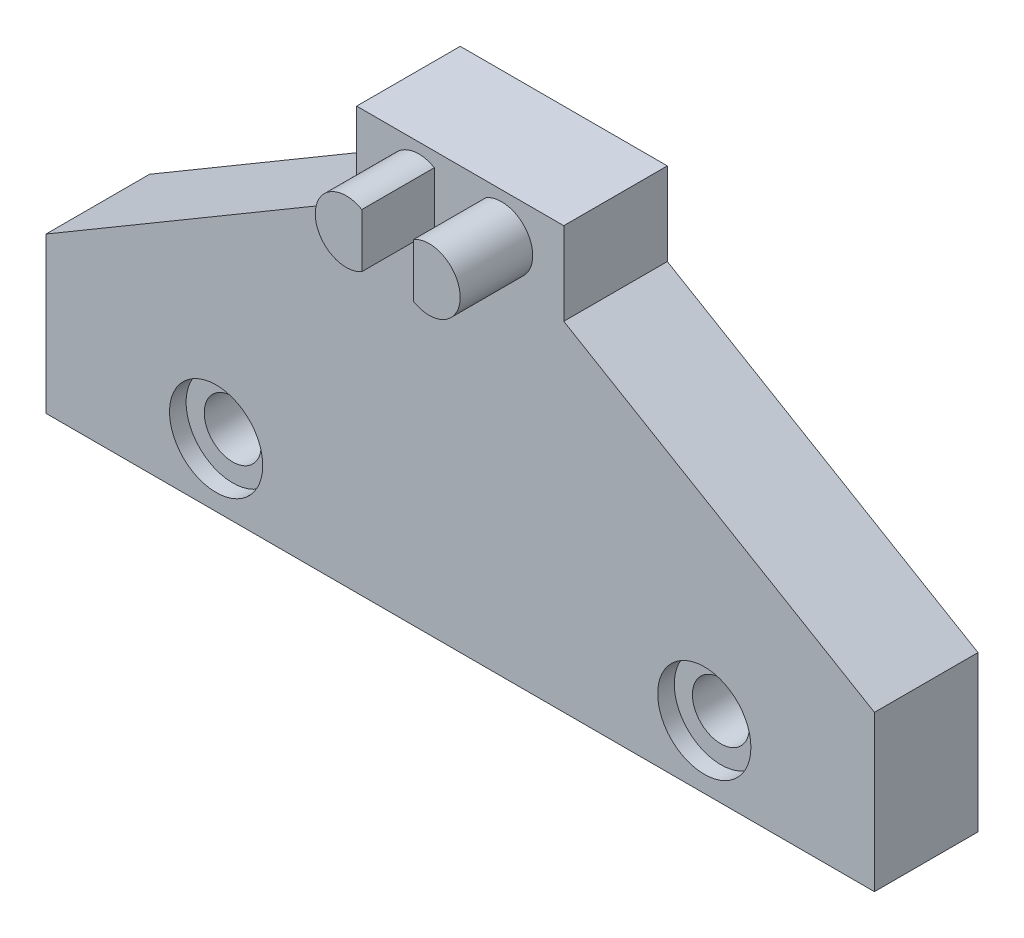
SolidWorks part; units mm, degrees
ref_plane "Front Plane" through (0, 0, 0) normal (0, 0, 1) x (1, 0, 0)
ref_plane "Top Plane" through (0, 0, 0) normal (0, 1, 0) x (1, 0, 0)
ref_plane "Right Plane" through (0, 0, 0) normal (1, 0, 0) x (0, 0, -1)
sketch "Sketch2" plane through (0, 0, 0) normal (0, 0, 1) x (1, 0, 0)
  line L0 (-24.3822, 22.6401) -> (-54.3822, 4.9401)
  line L2 (-54.3822, 4.9401) -> (-54.3822, -10.0599)
  line L3 (-54.3822, -10.0599) -> (25.6178, -10.0599)
  line L4 (25.6178, 4.9401) -> (25.6178, -10.0599)
  line L5 (-24.3822, 30.6401) -> (-4.3822, 30.6401)
  line L6 (-24.3822, 30.6401) -> (-24.3822, 22.6401)
  line L8 (-4.3822, 30.6401) -> (-4.3822, 22.6401)
  line L9 (-4.3822, 22.6401) -> (25.6178, 4.9401)
  point P8 (-14.3822, 30.6401)
  point P9 (-14.3822, -10.0599)
  dimension "D1" = 8
  dimension "D2" = 20
  dimension "D3" = 80
  dimension "D4" = 25.7
  dimension "D5" = 15
extrude "Boss-Extrude1" add sketch "Sketch2" along normal blind 10
sketch "Sketch3" plane through (0, 0, 10) normal (0, 0, 1) x (1, 0, 0)
  line L0 (-4.3822, 30.6401) -> (-24.3822, 30.6401) construction
  line L1 (-24.3822, 30.6401) -> (-24.3822, 22.6401) construction
  circle A0 centre (-18.3822, 26.6401) radius 3
  dimension "D1" = 6
  dimension "D3" = 6
  dimension "D2" = 4
extrude "Boss-Extrude2" add sketch "Sketch3" along normal blind 7
ref_plane "Plane1" through (-14.3822, 0, 0) normal (-1, 0, 0) x (0, 0, 1)
mirror "Mirror1" about plane through (-14.3822, 0, 0) normal (-1, 0, 0) of "Boss-Extrude2"
sketch "Sketch4" plane through (0, 0, 10) normal (0, 0, 1) x (1, 0, 0)
  line L0 (-54.3822, 4.9401) -> (-54.3822, -10.0599) construction
  circle A0 centre (-37.9522, -3.9599) radius 2.75
  dimension "D1" = 5.5
  dimension "D2" = 8.9
  dimension "D3" = 16.43
extrude "Cut-Extrude1" cut sketch "Sketch4" against normal through all
mirror "Mirror2" about plane through (-14.3822, 0, 0) normal (-1, 0, 0) of "Cut-Extrude1"
sketch "Sketch5" plane through (0, 0, 10) normal (0, 0, 1) x (1, 0, 0)
  line L0 (-54.3822, -10.0599) -> (25.6178, -10.0599) construction
  line L1 (-16.8822, -10.0599) -> (-11.8822, -10.0599)
  line L2 (-16.8822, -10.0599) -> (-16.8822, 30.6401)
  line L3 (-16.8822, 30.6401) -> (-11.8822, 30.6401)
  line L4 (-11.8822, -10.0599) -> (-11.8822, 30.6401)
  line L5 (-4.3822, 30.6401) -> (-24.3822, 30.6401) construction
  line L6 (-14.3822, 4.4) -> (-14.3822, -4.4) construction
  point P10 (-14.3822, 30.6401)
  dimension "D1" = 5
extrude "Cut-Extrude2" cut sketch "Sketch5" along normal up to surface (7 mm away) up to face at (-15.3822, 26.6401, 17)
sketch "Sketch6" plane through (0, 0, 10) normal (0, 0, 1) x (1, 0, 0)
  circle A0 centre (-37.9522, -3.9599) radius 4.5
  circle A1 centre (9.1878, -3.9599) radius 4.5
  dimension "D1" = 9
extrude "Cut-Extrude3" cut sketch "Sketch6" against normal blind 1.6
